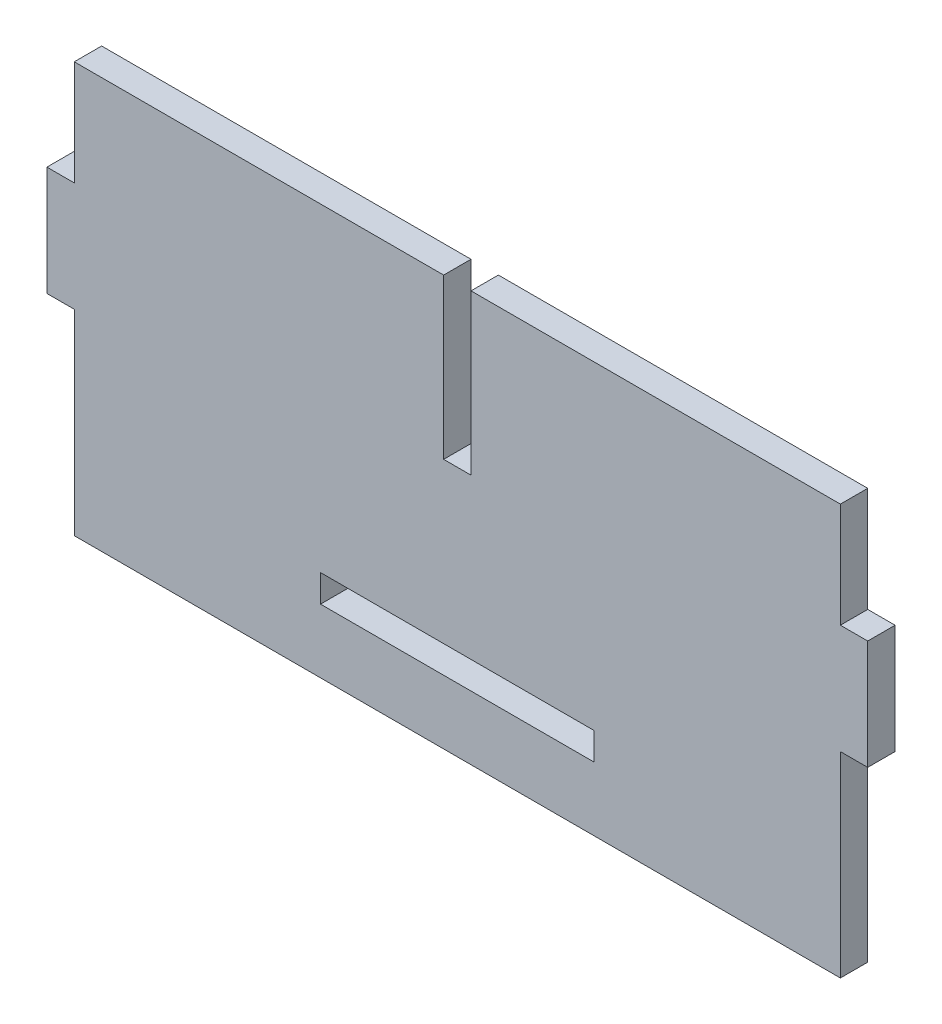
SolidWorks part; units mm, degrees
ref_plane "Front Plane" through (0, 0, 0) normal (0, 0, 1) x (1, 0, 0)
ref_plane "Top Plane" through (0, 0, 0) normal (0, 1, 0) x (1, 0, 0)
ref_plane "Right Plane" through (0, 0, 0) normal (1, 0, 0) x (0, 0, -1)
sketch "Sketch1" plane through (0, 0, 0) normal (0, 0, 1) x (1, 0, 0)
  line L0 (-45, -1) -> (-42, -1)
  line L1 (-45, -22.5) -> (45, -22.5)
  line L2 (-45, -22.5) -> (-45, 22.5)
  line L3 (-45, 22.5) -> (45, 22.5)
  line L4 (45, -22.5) -> (45, 22.5)
  line L5 (-45, -22.5) -> (45, 22.5) construction
  line L6 (-45, 22.5) -> (45, -22.5) construction
  line L7 (-42, -1) -> (-42, -22.5)
  line L8 (-42, 22.5) -> (-42, 11)
  line L9 (45, -1) -> (42, -1)
  line L10 (42, -1) -> (42, -22.5)
  line L11 (45, 11) -> (42, 11)
  line L12 (42, 11) -> (42, 22.5)
  line L13 (-42, 11) -> (-45, 11)
  line L14 (-1.5, 5) -> (1.5, 5)
  line L15 (-1.5, 5) -> (-1.5, 22.5)
  line L16 (-1.5, 22.5) -> (1.5, 22.5)
  line L17 (1.5, 5) -> (1.5, 22.5)
  line L18 (-1.5, 5) -> (1.5, 22.5) construction
  line L19 (-1.5, 22.5) -> (1.5, 5) construction
  line L21 (-15, -15.5) -> (15, -15.5)
  line L22 (-15, -15.5) -> (-15, -12.5)
  line L23 (-15, -12.5) -> (15, -12.5)
  line L24 (15, -15.5) -> (15, -12.5)
  line L25 (-15, -15.5) -> (15, -12.5) construction
  line L26 (-15, -12.5) -> (15, -15.5) construction
  point P0 (0, 0)
  point P15 (0, 0)
  point P17 (0, 13.75)
  point P23 (0, -14)
  dimension "D1" = 90
  dimension "D2" = 45
  dimension "D3" = 21.5
  dimension "D4" = 12
  dimension "D5" = 3
  dimension "D6" = 3
  dimension "D7" = 3
  dimension "D8" = 17.5
  dimension "D9" = 3
  dimension "D10" = 0
  dimension "D11" = 21.5
  dimension "D12" = 12
  dimension "D13" = 30
  dimension "D14" = 3
  dimension "D15" = 7
  dimension "D16" = 0
extrude "Boss-Extrude1" add sketch "Sketch1" along normal blind 3
